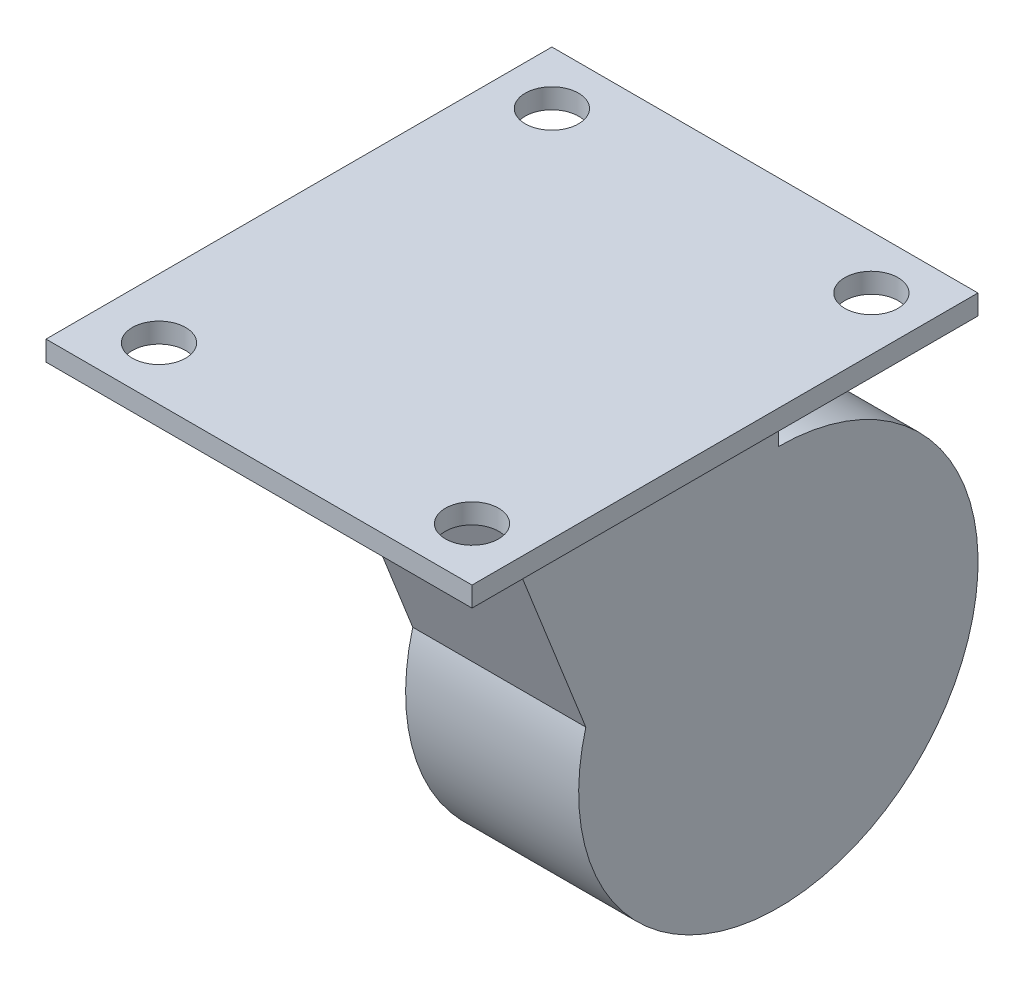
SolidWorks part; units mm, degrees
ref_plane "Front Plane" through (0, 0, 0) normal (0, 0, 1) x (1, 0, 0)
ref_plane "Top Plane" through (0, 0, 0) normal (0, 1, 0) x (1, 0, 0)
ref_plane "Right Plane" through (0, 0, 0) normal (1, 0, 0) x (0, 0, -1)
sketch "Sketch1" plane through (0, 0, 0) normal (0, 1, 0) x (1, 0, 0)
  line L1 (-12.8229, 14.9558) -> (19.1771, 14.9558)
  line L2 (-12.8229, 14.9558) -> (-12.8229, -23.0442)
  line L3 (-12.8229, -23.0442) -> (19.1771, -23.0442)
  line L4 (19.1771, 14.9558) -> (19.1771, -23.0442)
  circle A0 centre (-8.8229, 10.9558) radius 2
  circle A1 centre (15.1771, 10.9558) radius 2
  circle A2 centre (15.1771, -19.0442) radius 2
  circle A3 centre (-8.3366, -19.0442) radius 2
  point P6 (-8.1818, 11.7121)
  point P9 (13.7749, 11.7121)
  point P12 (13.7749, -16.0996)
  point P15 (-7.4499, -16.0996)
  point P16 (-5.2511, 12.5783)
  point P17 (-6.8587, -25.7156)
  point P18 (0, 0)
  point P19 (0, 0)
  point P20 (-6.8587, 2.7678)
  point P21 (-8.3366, -19.127)
  point P22 (-8.6873, 8.408)
  point P23 (15.1771, -19.0442)
  dimension "D3" = 4
  dimension "D1" = 32
  dimension "D2" = 38
  dimension "D4" = 4
  dimension "D5" = 4
  dimension "D6" = 24
  dimension "D7" = 30
extrude "Boss-Extrude1" add sketch "Sketch1" against normal blind 1.5
ref_plane "Plane1" through (3.1771, 0, 0) normal (-1, 0, 0) x (0, 0, 1)
sketch "Sketch2" plane through (3.1771, 0, 0) normal (-1, 0, 0) x (0, 0, 1)
  line L0 (-14.9558, 0) -> (23.0442, 0) construction
  line L1 (-9.4664, -1.5) -> (-9.4664, -12)
  line L2 (-14.9558, -1.5) -> (23.0442, -1.5) construction
  line L3 (-9.4664, -1.5) -> (13.4942, -1.5)
  line L4 (13.4942, -1.5) -> (4.9955, -23.0182)
  circle A0 centre (-9.4664, -27) radius 15
  dimension "D1" = 30
  dimension "D2" = 27
extrude "Boss-Extrude2" add sketch "Sketch2" along normal blind 6.5 and the other way blind 6.5 contours A0 | A0 L4 L3 L1
